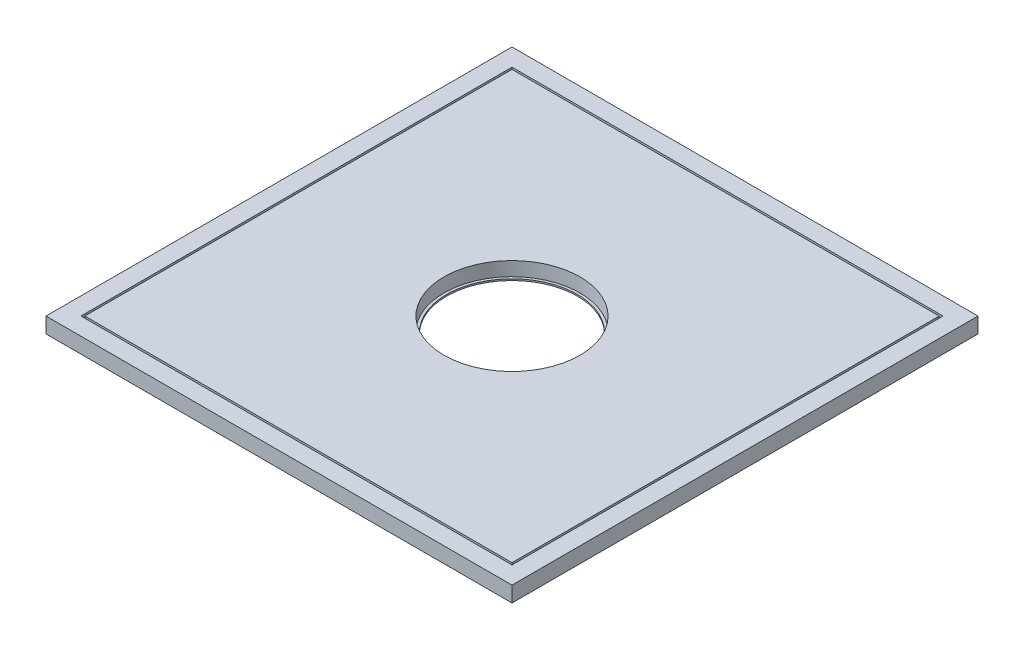
SolidWorks part; units mm, degrees
ref_plane "Front Plane" through (0, 0, 0) normal (0, 0, 1) x (1, 0, 0)
ref_plane "Top Plane" through (0, 0, 0) normal (0, 1, 0) x (1, 0, 0)
ref_plane "Right Plane" through (0, 0, 0) normal (1, 0, 0) x (0, 0, -1)
sketch "Sketch1" plane through (0, 0, 0) normal (0, 1, 0) x (1, 0, 0)
  line L1 (-300, 300) -> (300, 300)
  line L2 (-300, 300) -> (-300, -300)
  line L3 (-300, -300) -> (300, -300)
  line L4 (300, 300) -> (300, -300)
  line L5 (-300, 300) -> (300, -300) construction
  line L6 (-300, -300) -> (300, 300) construction
  point P0 (0, 0)
  dimension "D1" = 600
  dimension "600" = 600
extrude "plate" add sketch "Sketch1" along normal blind 20
sketch "Sketch2" plane through (0, 20, 0) normal (0, 1, 0) x (1, 0, 0)
  circle A0 centre (0, 0) radius 87.5
  dimension "D1" = 175
extrude "bearing-hole" cut sketch "Sketch2" against normal blind 18
sketch "Sketch3" plane through (0, 2, 0) normal (0, 1, 0) x (1, 0, 0)
  circle A0 centre (0, 0) radius 84.25
  dimension "D1" = 168.5
extrude "Cut-Extrude2" cut sketch "Sketch3" against normal blind 18
sketch "Sketch4" plane through (0, 20, 0) normal (0, 1, 0) x (1, 0, 0)
  line L1 (-277.5, 277.5) -> (277.5, 277.5)
  line L2 (-277.5, 277.5) -> (-277.5, -277.5)
  line L3 (-277.5, -277.5) -> (277.5, -277.5)
  line L4 (277.5, 277.5) -> (277.5, -277.5)
  line L5 (-277.5, 277.5) -> (277.5, -277.5) construction
  line L6 (-277.5, -277.5) -> (277.5, 277.5) construction
  line L7 (-275, 275) -> (275, 275)
  line L8 (-275, 275) -> (-275, -275)
  line L9 (-275, -275) -> (275, -275)
  line L10 (275, 275) -> (275, -275)
  line L11 (-275, 275) -> (275, -275) construction
  line L12 (-275, -275) -> (275, 275) construction
  point P0 (0, 0)
  point P6 (0, 0)
  dimension "D1" = 550
  dimension "D2" = 550
  dimension "D3" = 555
extrude "Cut-Extrude3" cut sketch "Sketch4" against normal blind 10
